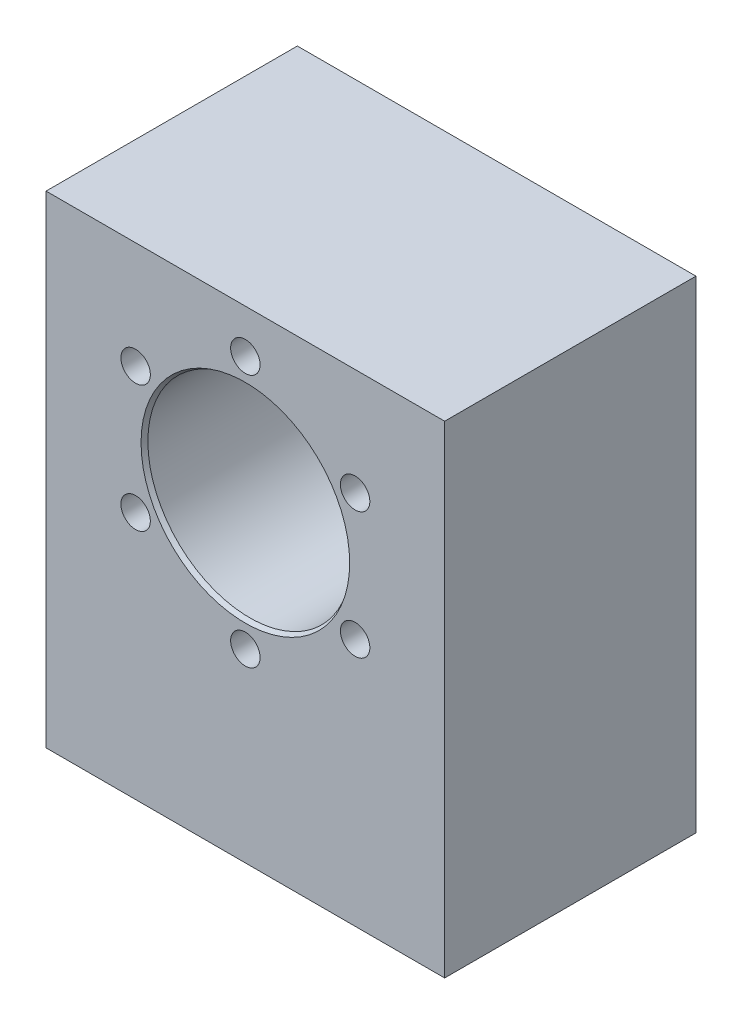
SolidWorks part; units mm, degrees
material "Low Carbon Steel"
ref_plane "Front Plane" through (0, 0, 0) normal (0, 0, 1) x (1, 0, 0)
ref_plane "Top Plane" through (0, 0, 0) normal (0, 1, 0) x (1, 0, 0)
ref_plane "Right Plane" through (0, 0, 0) normal (1, 0, 0) x (0, 0, -1)
sketch "Sketch2" plane through (0, 0, 0) normal (0, 0, 1) x (1, 0, 0)
  line L0 (0, 0) -> (0, -75) construction
  line L1 (-50.8, 39.3) -> (50.8, 39.3)
  line L2 (-50.8, 39.3) -> (-50.8, -75)
  line L3 (-50.8, -75) -> (50.8, -75)
  line L4 (50.8, 39.3) -> (50.8, -75)
  circle A0 centre (0, 0) radius 23.5 construction
  dimension "D2" = 47
  dimension "D1" = 75
  dimension "D3" = 114.3
  dimension "D4" = 101.6
extrude "Boss-Extrude1" add sketch "Sketch2" along normal blind 63.5
sketch "Sketch4" plane through (0, 39.3, 0) normal (0, 1, 0) x (1, 0, 0)
  line L0 (50.8, -63.5) -> (50.8, 0) construction
  line L1 (-50.8, -63.5) -> (50.8, -63.5)
  line L2 (-50.8, -63.5) -> (-50.8, -58)
  line L3 (-50.8, -58) -> (50.8, -58)
  line L4 (50.8, -63.5) -> (50.8, -58)
  line L5 (50.8, 0) -> (-50.8, 0) construction
  dimension "D1" = 58
extrude "Cut-Extrude2" cut sketch "Sketch4" against normal through all
sketch "Sketch6" plane through (0, 0, 58) normal (0, 0, 1) x (1, 0, 0)
  line L0 (50.8, -75) -> (50.8, 39.3) construction
  line L1 (-50.8, -75) -> (50.8, -75)
  line L2 (-50.8, -75) -> (-50.8, -72)
  line L3 (-50.8, -72) -> (50.8, -72)
  line L4 (50.8, -75) -> (50.8, -72)
  dimension "D1" = 72
extrude "Cut-Extrude4" cut sketch "Sketch6" against normal through all
sketch "Sketch3" plane through (0, 0, 58) normal (0, 0, 1) x (1, 0, 0)
  circle A0 centre (0, 0) radius 18
  dimension "D1" = 36
extrude "Cut-Extrude1" cut sketch "Sketch3" against normal through all
sketch "Sketch5" plane through (0, 0, 58) normal (0, 0, 1) x (1, 0, 0)
  circle A0 centre (0, 0) radius 23.5
  dimension "D1" = 47
extrude "Cut-Extrude3" cut sketch "Sketch5" against normal blind 46.24
hole_wizard "M8 Tapped Hole1" positions "Sketch8" profile "Sketch7" tap size "M8" standard "Peddi DIN"
sketch "Sketch8" plane through (0, 0, 58) normal (0, 0, 1) x (1, 0, 0)
  line L1 (25.3312, 14.625) -> (0, 29.25) construction
  line L2 (0, 29.25) -> (-25.3312, 14.625) construction
  line L3 (-25.3312, 14.625) -> (-25.3312, -14.625) construction
  line L4 (-25.3312, -14.625) -> (0, -29.25) construction
  line L5 (0, -29.25) -> (25.3312, -14.625) construction
  line L6 (25.3312, -14.625) -> (25.3312, 14.625) construction
  line L9 (0, 0) -> (0, 29.25) construction
  circle A2 centre (0, 0) radius 29.25 construction
  circle A3 centre (0, 0) radius 25.3312 construction
  point P0 (0, 29.25)
  point P2 (25.3312, 14.625)
  point P4 (25.3312, -14.625)
  point P6 (0, -29.25)
  point P8 (-25.3312, -14.625)
  point P10 (-25.3312, 14.625)
  point P14 (25.3312, 14.625)
  dimension "D1" = 58.5
sketch "Sketch7" plane through (0, 29.25, 58) normal (1, 0, 0) x (0, -1, 0)
  line L0 (0, 0) -> (0, 28.3929)
  line L1 (0, 28.3929) -> (3.4, 26.35)
  line L2 (3.4, 26.35) -> (3.4, 0)
  line L5 (3.4, 0) -> (0, 0)
  line L10 (0, 28.3929) -> (-3.4, 26.35) construction
  line L11 (0, -6.35) -> (0, 107.95) construction
  dimension "Tap Drill Dia." = 6.8
  dimension "Tap Drill Depth" = 26.35
  dimension "Drill Angle" = 118
cosmetic thread "Hole Thread1" parameters "D1"=20, "D2"=8
cosmetic thread "Hole Thread3" parameters "D1"=20, "D2"=8
cosmetic thread "Hole Thread4" parameters "D1"=20, "D2"=8
cosmetic thread "Hole Thread5" parameters "D1"=20, "D2"=8
cosmetic thread "Hole Thread6" parameters "D1"=20, "D2"=8
cosmetic thread "Hole Thread7" parameters "D1"=20, "D2"=8
cosmetic thread "Hole Thread14" parameters "D1"=20, "D2"=8
chamfer "Chamfer1" distance 1 angle 30 1 edges at (23.5, 0, 58)
sketch "Sketch9" plane through (0, 0, 58) normal (0, 0, 1) x (1, 0, 0)
  circle A0 centre (0, 0) radius 19
  dimension "D1" = 38
extrude "Cut-Extrude6" cut sketch "Sketch9" against normal blind 1.6 from offset 48.5 offset against normal yes
sketch "Sketch10" plane through (0, -72, 0) normal (0, -1, 0) x (1, 0, 0)
  line L0 (0, 24) -> (0, 0) construction
  line L1 (-25.4, 36) -> (25.4, 36)
  line L2 (-25.4, 36) -> (-25.4, 24) construction
  line L3 (-25.4, 24) -> (25.4, 24)
  line L4 (25.4, 36) -> (25.4, 24) construction
  line L5 (50.8, 0) -> (-50.8, 0) construction
  line L6 (50.8, 58) -> (-50.8, 58) construction
  arc A0 (-25.4, 36) -> (-25.4, 24) centre (-25.4, 30) ccw
  arc A1 (25.4, 24) -> (25.4, 36) centre (25.4, 30) ccw
  dimension "D1" = 12
  dimension "D2" = 50.8
  dimension "D3" = 22
extrude "Cut-Extrude7" cut sketch "Sketch10" against normal blind 5.08
hole_wizard "M12 Tapped Hole1" positions "Sketch12" profile "Sketch11" tap size "M12" standard "Peddi DIN"
sketch "Sketch12" plane through (0, -72, 0) normal (0, -1, 0) x (-1, 0, 0)
  line L0 (-31, -14) -> (31, -14) construction
  line L3 (-50.8, 0) -> (50.8, 0) construction
  line L4 (31, -14) -> (31, -46) construction
  line L5 (31, -46) -> (-31, -46) construction
  line L7 (0, 0) -> (0, -14) construction
  line L8 (-50.8, -58) -> (50.8, -58) construction
  point P0 (31, -46)
  point P2 (-31, -46)
  point P4 (-31, -14)
  point P6 (31, -14)
  dimension "D1" = 12
  dimension "D2" = 14
  dimension "D3" = 32
  dimension "D4" = 62
sketch "Sketch11" plane through (-31, -72, 46) normal (1, 0, 0) x (0, 0, -1)
  line L0 (0, 0) -> (0, 35.8144)
  line L1 (0, 35.8144) -> (5.1, 32.75)
  line L2 (5.1, 32.75) -> (5.1, 0)
  line L5 (5.1, 0) -> (0, 0)
  line L10 (0, 35.8144) -> (-5.1, 32.75) construction
  line L11 (0, -6.35) -> (0, 107.95) construction
  dimension "Tap Drill Dia." = 10.2
  dimension "Tap Drill Depth" = 32.75
  dimension "Drill Angle" = 118
cosmetic thread "Hole Thread9" parameters "D1"=30, "D2"=12
cosmetic thread "Hole Thread10" parameters "D1"=30, "D2"=12
cosmetic thread "Hole Thread11" parameters "D1"=30, "D2"=12
cosmetic thread "Hole Thread12" parameters "D1"=30, "D2"=12
sketch "Sketch14" plane through (0, 0, 0) normal (0, 0, -1) x (-1, 0, 0)
  line L0 (-50.8, -72) -> (50.8, -72) construction
  line L1 (-50.8, 39.3) -> (-46, 39.3)
  line L2 (-50.8, 39.3) -> (-50.8, -72)
  line L3 (-50.8, -72) -> (-46, -72)
  line L4 (-46, 39.3) -> (-46, -72)
  line L6 (50.8, 39.3) -> (46, 39.3)
  line L7 (50.8, 39.3) -> (50.8, -72)
  line L8 (50.8, -72) -> (46, -72)
  line L9 (46, 39.3) -> (46, -72)
  dimension "D1" = 92
extrude "Cut-Extrude8" cut sketch "Sketch14" against normal through all
fillet "Fillet1" radius 0.7937 4 edges at (-31.4, -66.92, 30) (0, -66.92, 36) (31.4, -66.92, 30) (0, -66.92, 24)
sketch "Sketch15" plane through (0, 0, 11.76) normal (0, 0, 1) x (1, 0, 0)
  circle A0 centre (0, 0) radius 23.5 construction
  circle A1 centre (0, 0) radius 23.5
  circle A2 centre (0, 0) radius 24.008
  dimension "D1" = 0.508
extrude "Cut-Extrude9" cut sketch "Sketch15" along normal blind 1.2954
other "Freeze***"
